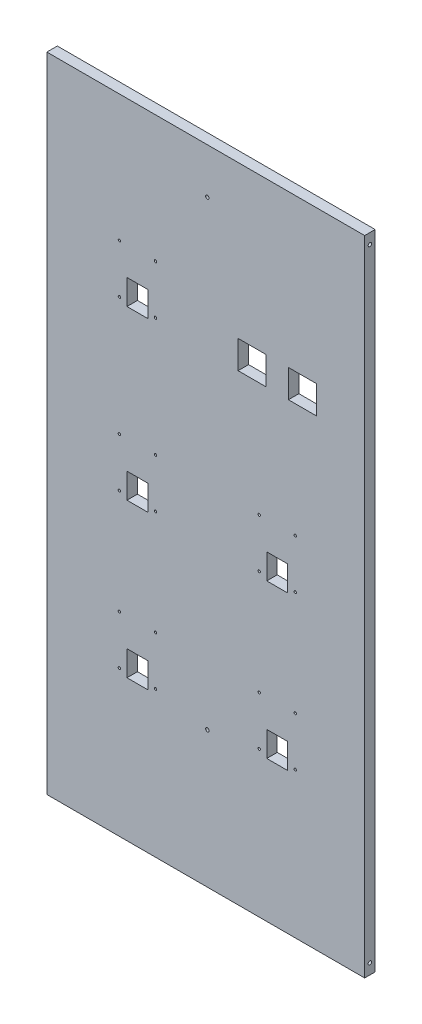
SolidWorks part; units mm, degrees
ref_plane "Alzado" through (0, 0, 0) normal (0, 0, 1) x (1, 0, 0)
ref_plane "Planta" through (0, 0, 0) normal (0, 1, 0) x (1, 0, 0)
ref_plane "Vista lateral" through (0, 0, 0) normal (1, 0, 0) x (0, 0, -1)
sketch "Croquis1" plane through (0, 0, 0) normal (0, 0, 1) x (1, 0, 0)
  line L1 (250, -460) -> (-250, -460)
  line L2 (250, -460) -> (250, 460)
  line L3 (250, 460) -> (-250, 460)
  line L4 (-250, -460) -> (-250, 460)
  line L5 (250, -460) -> (-250, 460) construction
  line L6 (250, 460) -> (-250, -460) construction
  point P0 (0, 0)
  dimension "D1" = 500
  dimension "D2" = 920
extrude "Saliente-Extruir1" add sketch "Croquis1" along normal blind 15
sketch "Croquis2" plane through (0, 0, 15) normal (0, 0, 1) x (1, 0, 0)
  line L0 (-200, 410) -> (-200, -280) construction
  line L1 (-200, -280) -> (200, -280) construction
  line L2 (200, -280) -> (200, 410) construction
  line L3 (200, 410) -> (-200, 410) construction
  line L4 (-250, 460) -> (-250, -460) construction
  line L5 (250, -460) -> (250, 460) construction
  line L6 (-200, 180) -> (200, 180) construction
  line L7 (200, 180) -> (200, -50) construction
  line L12 (200, -50) -> (-200, -50) construction
  line L13 (0, 410) -> (0, -280) construction
  line L14 (250, 460) -> (-250, 460) construction
  circle A0 centre (0, -265) radius 2.5
  circle A5 centre (0, 395) radius 2.5
  dimension "D9" = 5
  dimension "D12" = 5
  dimension "D3" = 50
  dimension "D2" = 400
  dimension "D1" = 690
  dimension "D4" = 50
  dimension "D5" = 50
  dimension "D6" = 230
  dimension "D7" = 230
  dimension "D8" = 690
  dimension "D10" = 15
  dimension "D11" = 15
extrude "Cortar-Extruir1" cut sketch "Croquis2" against normal through all
sketch "Croquis3" plane through (250, 0, 0) normal (1, 0, 0) x (0, 0, -1)
  line L0 (0, 0) -> (-15, 0) construction
  line L1 (-15, -460) -> (-15, 460) construction
  line L2 (-7.5, 460) -> (-7.5, 445) construction
  line L3 (-15, 460) -> (0, 460) construction
  circle A0 centre (-7.5, 445) radius 2.5
  circle A1 centre (-7.5, -445) radius 2.5
  dimension "D2" = 5
  dimension "D1" = 15
extrude "Cortar-Extruir2" cut sketch "Croquis3" against normal through all
sketch "Croquis5" plane through (0, 0, 0) normal (0, 0, -1) x (-1, 0, 0)
  line L0 (115, 202) -> (85, 202)
  line L1 (200, 180) -> (-200, 180) construction
  line L6 (115, 202) -> (115, 238)
  line L7 (-200, -280) -> (-200, 410) construction
  line L8 (-100, 438.3069) -> (-100, -280) construction
  line L9 (200, -280) -> (-200, -280) construction
  line L10 (-100, 220) -> (-100, 180) construction
  line L11 (-125.8, 220) -> (-74.2, 220) construction
  line L12 (-85, 202) -> (-115, 202)
  line L13 (-85, 202) -> (-85, 238)
  line L14 (-85, 238) -> (-115, 238)
  line L15 (-115, 202) -> (-115, 238)
  line L16 (-85, 202) -> (-115, 238) construction
  line L17 (-85, 238) -> (-115, 202) construction
  line L18 (-74.2, 220) -> (-74.2, 208.5) construction
  line L19 (-74.2, 208.5) -> (-74.2, 278.5) construction
  line L20 (-125.8, 208.5) -> (-125.8, 278.5) construction
  line L21 (-125.8, 220) -> (-125.8, 208.5) construction
  line L22 (115, 238) -> (85, 238)
  line L23 (85, 202) -> (85, 238)
  line L24 (100, 457.5069) -> (100, 199.2) construction
  line L25 (100, 229.2) -> (100, 199.2) construction
  line L26 (74.2, 220) -> (125.8, 220) construction
  line L27 (115, 202) -> (85, 238) construction
  line L28 (115, 238) -> (85, 202) construction
  line L29 (125.8, 220) -> (125.8, 208.5) construction
  line L30 (125.8, 208.5) -> (125.8, 278.5) construction
  line L31 (74.2, 208.5) -> (74.2, 278.5) construction
  line L32 (74.2, 220) -> (74.2, 208.5) construction
  line L33 (115, -38) -> (85, -38)
  line L34 (115, -38) -> (115, -2)
  line L35 (115, -2) -> (85, -2)
  line L36 (85, -38) -> (85, -2)
  line L37 (100, 222.9069) -> (100, 199.2) construction
  line L38 (100, -5.4) -> (100, -35.4) construction
  line L39 (74.2, -20) -> (125.8, -20) construction
  line L40 (115, -38) -> (85, -2) construction
  line L41 (115, -2) -> (85, -38) construction
  line L42 (125.8, -20) -> (125.8, -31.5) construction
  line L43 (125.8, -31.5) -> (125.8, 38.5) construction
  line L44 (74.2, -31.5) -> (74.2, 38.5) construction
  line L45 (74.2, -20) -> (74.2, -31.5) construction
  line L46 (115, -258) -> (85, -258)
  line L47 (115, -258) -> (115, -222)
  line L48 (115, -222) -> (85, -222)
  line L49 (85, -258) -> (85, -222)
  line L50 (100, -11.6931) -> (100, -35.4) construction
  line L51 (100, -259.2) -> (100, -289.2) construction
  line L52 (74.2, -240) -> (125.8, -240) construction
  line L53 (115, -258) -> (85, -222) construction
  line L54 (115, -222) -> (85, -258) construction
  line L55 (125.8, -240) -> (125.8, -251.5) construction
  line L56 (125.8, -251.5) -> (125.8, -181.5) construction
  line L57 (74.2, -251.5) -> (74.2, -181.5) construction
  line L58 (74.2, -240) -> (74.2, -251.5) construction
  line L59 (-85, -38) -> (-115, -38)
  line L60 (-85, -38) -> (-85, -2)
  line L61 (-85, -2) -> (-115, -2)
  line L62 (-115, -38) -> (-115, -2)
  line L63 (-100, 203.7069) -> (-100, -514.6) construction
  line L64 (-100, -20) -> (-100, -50) construction
  line L65 (-125.8, -20) -> (-74.2, -20) construction
  line L66 (-85, -38) -> (-115, -2) construction
  line L67 (-85, -2) -> (-115, -38) construction
  line L68 (-74.2, -20) -> (-74.2, -31.5) construction
  line L69 (-74.2, -31.5) -> (-74.2, 38.5) construction
  line L70 (-125.8, -31.5) -> (-125.8, 38.5) construction
  line L71 (-125.8, -20) -> (-125.8, -31.5) construction
  line L72 (-85, -258) -> (-115, -258)
  line L73 (-85, -258) -> (-85, -222)
  line L74 (-85, -222) -> (-115, -222)
  line L75 (-115, -258) -> (-115, -222)
  line L76 (-100, -30.8931) -> (-100, -749.2) construction
  line L77 (-100, -259.2) -> (-100, -289.2) construction
  line L78 (-125.8, -240) -> (-74.2, -240) construction
  line L79 (-85, -258) -> (-115, -222) construction
  line L80 (-85, -222) -> (-115, -258) construction
  line L81 (-74.2, -240) -> (-74.2, -251.5) construction
  line L82 (-74.2, -251.5) -> (-74.2, -181.5) construction
  line L83 (-125.8, -251.5) -> (-125.8, -181.5) construction
  line L84 (-125.8, -240) -> (-125.8, -251.5) construction
  line L85 (-200, -50) -> (200, -50) construction
  line L86 (100, -2) -> (100, -35.4) construction
  line L87 (100, -2) -> (100, -35.4) construction
  line L88 (100, -222) -> (100, -260.8) construction
  line L89 (100, -222) -> (100, -495.4) construction
  line L90 (100, -222) -> (100, -730) construction
  circle A0 centre (-74.2, 208.5) radius 1.75
  circle A1 centre (-74.2, 278.5) radius 1.75
  circle A2 centre (-125.8, 278.5) radius 1.75
  circle A3 centre (-125.8, 208.5) radius 1.75
  circle A4 centre (125.8, 208.5) radius 1.75
  circle A5 centre (125.8, 278.5) radius 1.75
  circle A6 centre (74.2, 278.5) radius 1.75
  circle A7 centre (74.2, 208.5) radius 1.75
  circle A8 centre (125.8, -31.5) radius 1.75
  circle A9 centre (125.8, 38.5) radius 1.75
  circle A10 centre (74.2, 38.5) radius 1.75
  circle A11 centre (74.2, -31.5) radius 1.75
  circle A12 centre (125.8, -251.5) radius 1.75
  circle A13 centre (125.8, -181.5) radius 1.75
  circle A14 centre (74.2, -181.5) radius 1.75
  circle A15 centre (74.2, -251.5) radius 1.75
  circle A16 centre (-74.2, -31.5) radius 1.75
  circle A17 centre (-74.2, 38.5) radius 1.75
  circle A18 centre (-125.8, 38.5) radius 1.75
  circle A19 centre (-125.8, -31.5) radius 1.75
  circle A20 centre (-74.2, -251.5) radius 1.75
  circle A21 centre (-74.2, -181.5) radius 1.75
  circle A22 centre (-125.8, -181.5) radius 1.75
  circle A23 centre (-125.8, -251.5) radius 1.75
  dimension "D8" = 3.5
  dimension "D10" = 3.5
  dimension "D2" = 100
  dimension "D3" = 22
  dimension "D4" = 18
  dimension "D5" = 15
  dimension "D6" = 25.8
  dimension "D7" = 11.5
  dimension "D9" = 70
  dimension "D13" = 12
  dimension "D14" = 6.5
  dimension "D15" = 6.5
  dimension "D11" = 12
  dimension "D12" = 6.5
  dimension "D16" = 22
  dimension "D17" = 6.5
  dimension "D18" = 22
  dimension "D19" = 22
extrude "Cortar-Extruir3" cut sketch "Croquis5" against normal through all
sketch "Croquis6" plane through (0, 0, 0) normal (0, 0, -1) x (-1, 0, 0)
  line L1 (-64.0178, 199.3374) -> (-132.5941, 199.3374)
  line L2 (-64.0178, 199.3374) -> (-64.0178, 289.5519)
  line L3 (-64.0178, 289.5519) -> (-132.5941, 289.5519)
  line L4 (-132.5941, 199.3374) -> (-132.5941, 289.5519)
extrude "Saliente-Extruir2" add sketch "Croquis6" against normal up to surface (15 mm away) up to face at (-127.55, 38.5, 15)
sketch "Croquis7" plane through (0, 0, 0) normal (0, 0, -1) x (-1, 0, 0)
  line L0 (-100, -38) -> (-100, 357.0568) construction
  line L1 (-115, -38) -> (-85, -38) construction
  line L3 (-84, 242) -> (-44, 242)
  line L4 (-84, 242) -> (-84, 202)
  line L5 (-84, 202) -> (-44, 202)
  line L6 (-44, 242) -> (-44, 202)
  line L8 (85, 202) -> (115, 202) construction
  line L9 (-156, 242) -> (-156, 202)
  line L10 (-116, 202) -> (-156, 202)
  line L11 (-116, 242) -> (-116, 202)
  line L12 (-116, 242) -> (-156, 242)
  dimension "D1" = 40
  dimension "D2" = 40
  dimension "D3" = 16
extrude "Cortar-Extruir4" cut sketch "Croquis7" against normal up to surface (15 mm away) up to face at (-127.55, 38.5, 15)
sketch "Croquis8" plane through (0, 0, 0) normal (0, 0, -1) x (-1, 0, 0)
  line L0 (250, -460) -> (-250, -460) construction
  line L1 (250, 460) -> (229.65, 460)
  line L2 (250, 460) -> (250, -460)
  line L3 (250, -460) -> (229.65, -460)
  line L4 (229.65, 460) -> (229.65, -460)
  line L6 (-250, 460) -> (-225.09, 460)
  line L7 (-250, 460) -> (-250, -460)
  line L8 (-250, -460) -> (-225.09, -460)
  line L9 (-225.09, 460) -> (-225.09, -460)
  dimension "D1" = 20.35
  dimension "D2" = 24.91
extrude "Cortar-Extruir5" cut sketch "Croquis8" against normal up to surface (15 mm away)
